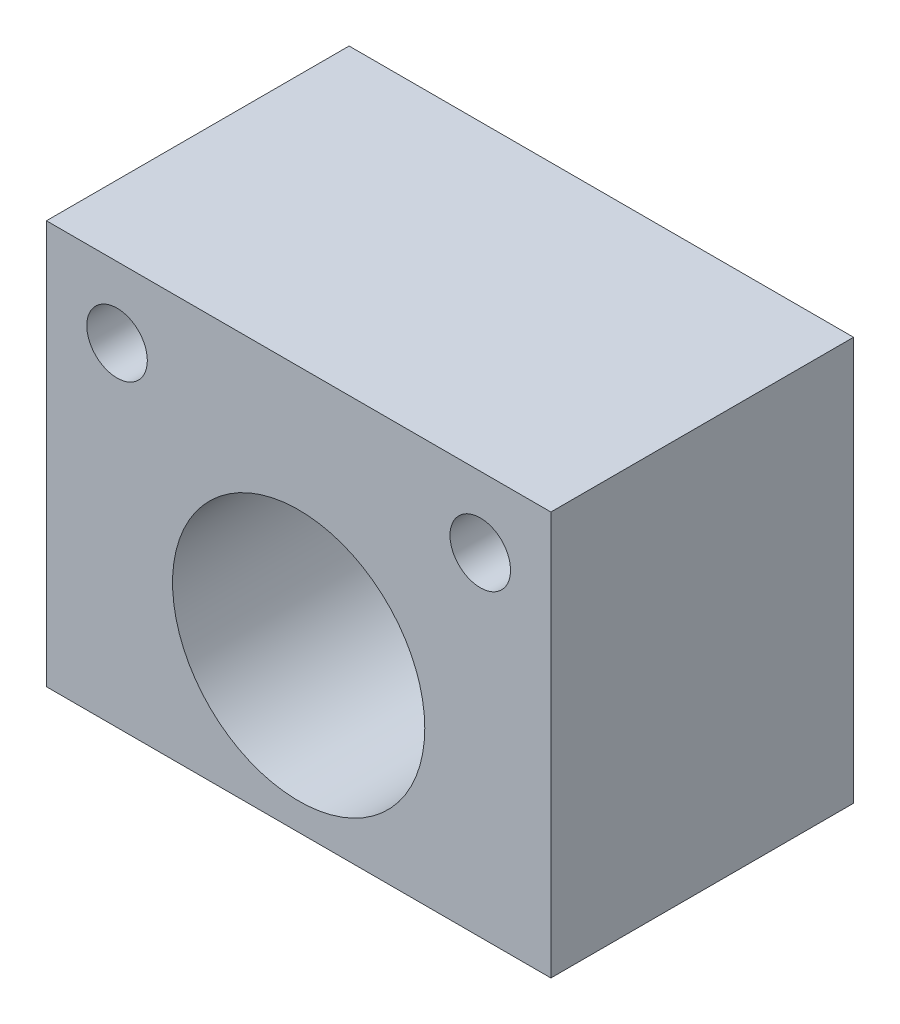
SolidWorks part; units mm, degrees
ref_plane "Alzado" through (0, 0, 0) normal (0, 0, 1) x (1, 0, 0)
ref_plane "Planta" through (0, 0, 0) normal (0, 1, 0) x (1, 0, 0)
ref_plane "Vista lateral" through (0, 0, 0) normal (1, 0, 0) x (0, 0, -1)
sketch "Croquis1" plane through (0, 0, 0) normal (0, 0, 1) x (1, 0, 0)
  line L1 (-25, 20) -> (25, 20)
  line L2 (-25, 20) -> (-25, -20)
  line L3 (-25, -20) -> (25, -20)
  line L4 (25, 20) -> (25, -20)
  line L5 (-25, 20) -> (25, -20) construction
  line L6 (-25, -20) -> (25, 20) construction
  circle A0 centre (0, 0) radius 12.5
  point P0 (0, 0)
  dimension "D3" = 25
  dimension "D1" = 40
  dimension "D2" = 50
extrude "Saliente-Extruir1" add sketch "Croquis1" along normal blind 30
sketch "Croquis2" plane through (0, 0, 30) normal (0, 0, 1) x (1, 0, 0)
  line L0 (25, 20) -> (-25, 20) construction
  line L2 (-25, 20) -> (-25, -20) construction
  circle A0 centre (-18, 13) radius 3
  circle A1 centre (18, 13) radius 3
  dimension "D1" = 6
  dimension "D2" = 7
  dimension "D3" = 7
extrude "Cortar-Extruir1" cut sketch "Croquis2" against normal blind 30
sketch "Croquis3" plane through (0, 0, 30) normal (0, 0, 1) x (1, 0, 0)
  circle A0 centre (0, 0) radius 12.5
extrude "Saliente-Extruir2" add sketch "Croquis3" against normal up to surface (30 mm away) up to face at (15, 13, 0)
sketch "Croquis4" plane through (0, 0, 30) normal (0, 0, 1) x (1, 0, 0)
  circle A0 centre (0, -4.8091) radius 12.5
  dimension "D1" = 25
extrude "Cortar-Extruir2" cut sketch "Croquis4" against normal offset from surface (20.1 mm away) 9.9 up to face at (15, 13, 0)
sketch "Croquis5" plane through (0, 0, 9.9) normal (0, 0, 1) x (1, 0, 0)
  circle A0 centre (0, -4.8091) radius 12.5
extrude "Cortar-Extruir3" cut sketch "Croquis5" against normal blind 9.9
